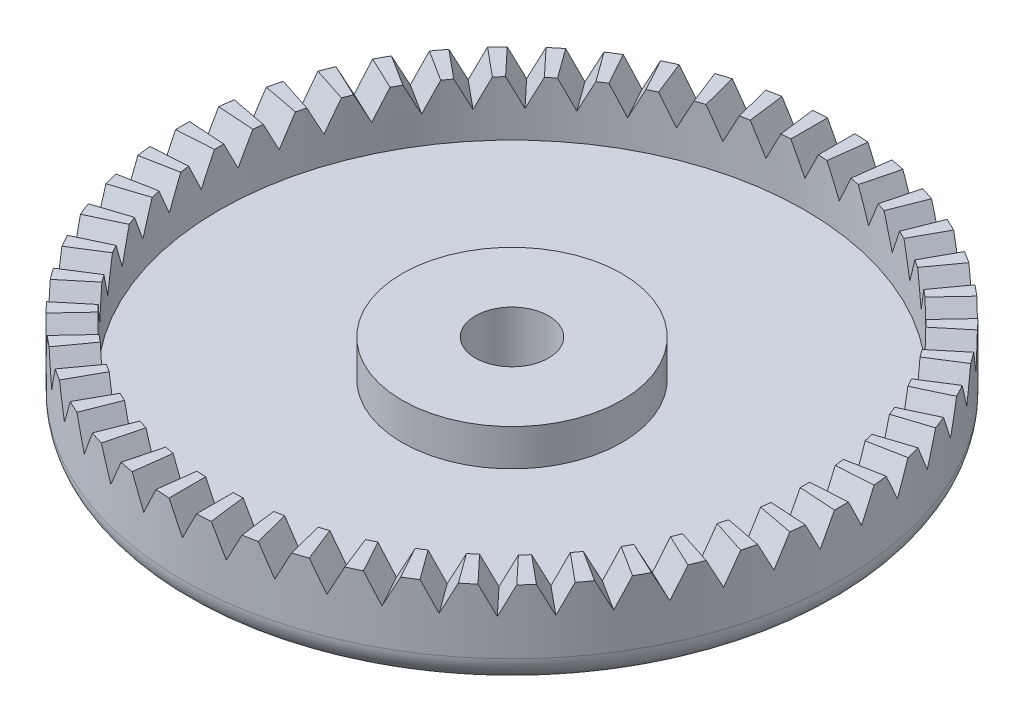
SolidWorks part; units mm, degrees
ref_plane "Plan de face" through (0, 0, 0) normal (0, 0, 1) x (1, 0, 0)
ref_plane "Plan de dessus" through (0, 0, 0) normal (0, 1, 0) x (1, 0, 0)
ref_plane "Plan de droite" through (0, 0, 0) normal (1, 0, 0) x (0, 0, -1)
sketch "Esquisse1" plane through (0, 0, 0) normal (0, 0, 1) x (1, 0, 0)
  line L0 (0, 0) -> (0, 11) construction
  line L1 (2, 0) -> (2, 11)
  line L2 (2, 11) -> (6, 11)
  line L3 (6, 11) -> (6, 9)
  line L4 (6, 9) -> (16, 9)
  line L5 (16, 9) -> (16, 12)
  line L6 (16, 12) -> (18, 12)
  line L7 (18, 12) -> (18, 8.5)
  line L8 (16.5, 7) -> (4.75, 7)
  line L9 (4.75, 7) -> (4.75, 0)
  line L10 (4.75, 0) -> (2, 0)
  arc A0 (18, 8.5) -> (16.5, 7) centre (16.5, 8.5) cw
  dimension "D10" = 1.5
  dimension "D1" = 4
  dimension "D2" = 9.5
  dimension "D3" = 12
  dimension "D4" = 11
  dimension "D5" = 5
  dimension "D6" = 7
  dimension "D7" = 36
  dimension "D8" = 32
  dimension "D9" = 2
revolve "Révolution1" add sketch "Esquisse1" angle 360 about L0
sketch "Esquisse2" plane through (0, 0, 0) normal (0, 0, 1) x (1, 0, 0)
  line L0 (-0.75, 12) -> (0.75, 12)
  line L1 (0.75, 12) -> (0, 10.5)
  line L2 (0, 10.5) -> (-0.75, 12)
  line L3 (18, 12) -> (-18, 12) construction
  dimension "D1" = 1.5
  dimension "D2" = 1.5
extrude "Enlèv. mat.-Extru.1" cut sketch "Esquisse2" along normal blind 15 from offset 10
pattern_circular "Répétition circulaire1" count 50 over 360 about axis through (0, 0, 0) along (0, 1, 0) of "Enlèv. mat.-Extru.1"
